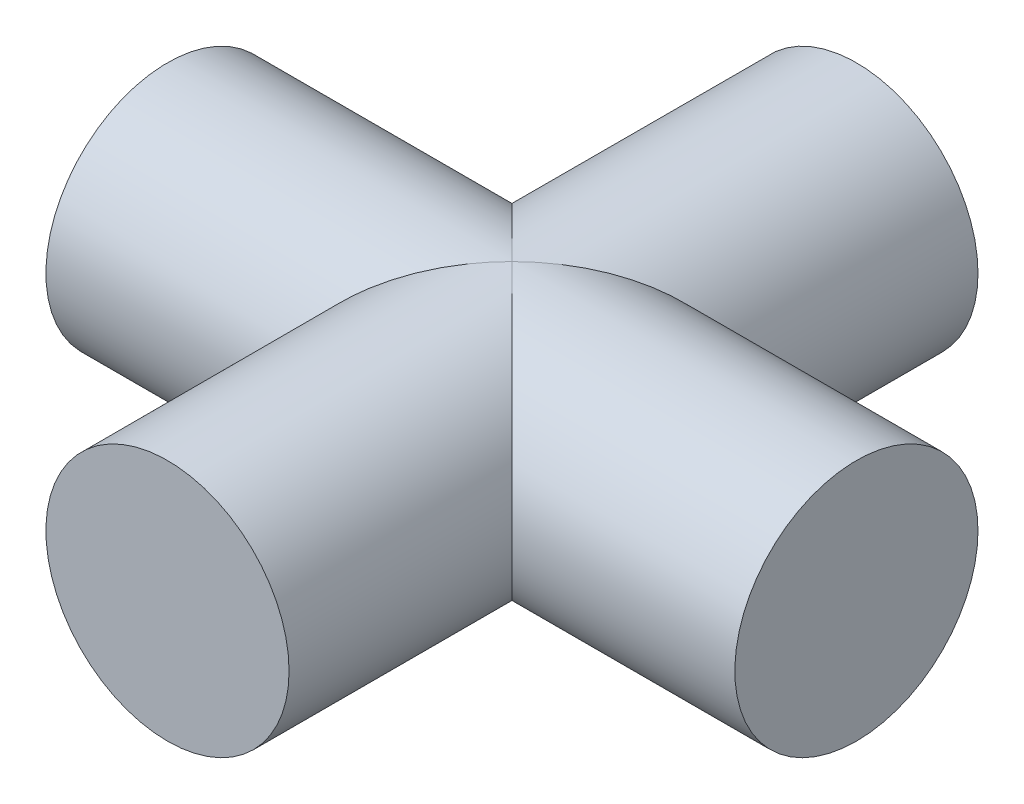
SolidWorks part; units mm, degrees
ref_plane "Front Plane" through (0, 0, 0) normal (0, 0, 1) x (1, 0, 0)
ref_plane "Top Plane" through (0, 0, 0) normal (0, 1, 0) x (1, 0, 0)
ref_plane "Right Plane" through (0, 0, 0) normal (1, 0, 0) x (0, 0, -1)
sketch "Sketch1" plane through (0, 0, 0) normal (0, 0, 1) x (1, 0, 0)
  circle A0 centre (0, 0) radius 4.765
  dimension "D1" = 9.53
extrude "Boss-Extrude3" add sketch "Sketch1" along normal mid plane 27
sketch "Sketch3" plane through (0, 0, 0) normal (1, 0, 0) x (0, 0, -1)
  circle A0 centre (0, 0) radius 4.765
extrude "Boss-Extrude4" add sketch "Sketch3" along normal mid plane 27
